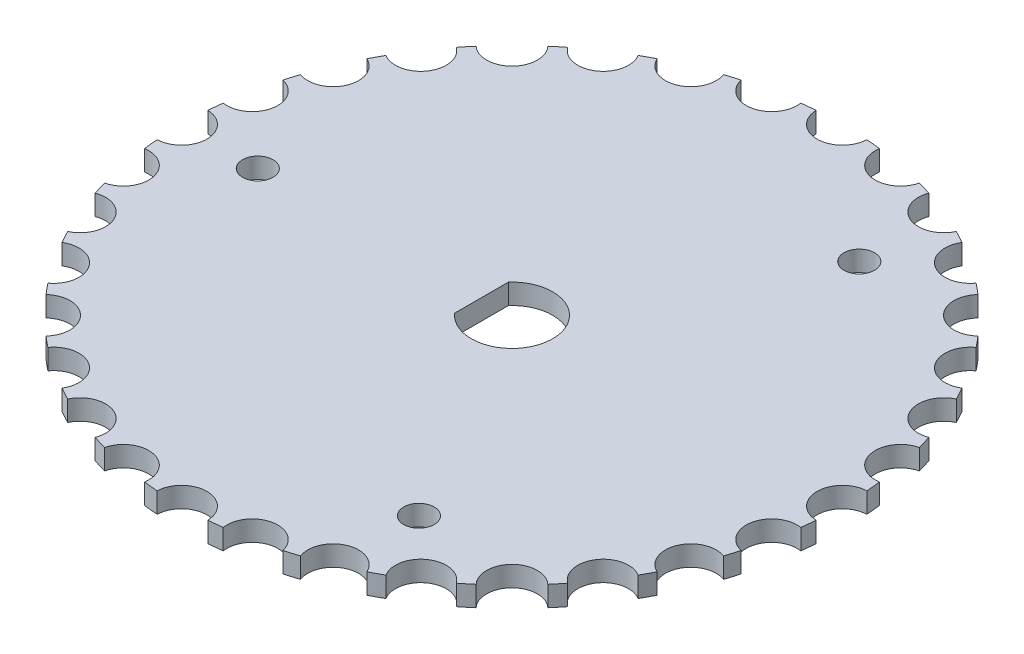
SolidWorks part; units mm, degrees
ref_plane "Front Plane" through (0, 0, 0) normal (0, 0, 1) x (1, 0, 0)
ref_plane "Top Plane" through (0, 0, 0) normal (0, 1, 0) x (1, 0, 0)
ref_plane "Right Plane" through (0, 0, 0) normal (1, 0, 0) x (0, 0, -1)
sketch "Sketch1" plane through (0, 0, 0) normal (0, 1, 0) x (1, 0, 0)
  circle A0 centre (0, 0) radius 32.5
  dimension "D1" = 65
extrude "Boss-Extrude1" add sketch "Sketch1" along normal blind 2
sketch "Sketch4" plane through (0, 2, 0) normal (0, 1, 0) x (1, 0, 0)
  line L0 (-3, -2.6458) -> (-3, 2.6458)
  arc A0 (-3, -2.6458) -> (-3, 2.6458) centre (0, 0) ccw
  dimension "D1" = 8
  dimension "D2" = 3
extrude "Cut-Extrude2" cut sketch "Sketch4" against normal through all
sketch "Sketch2" plane through (0, 2, 0) normal (0, 1, 0) x (1, 0, 0)
  circle A1 centre (-30.0261, -12.4372) radius 2.5
  circle A31 centre (-32.5, 0) radius 2.5
  circle A32 centre (0, 0) radius 32.5 construction
  circle A33 centre (-31.8755, 6.3404) radius 2.5
  circle A34 centre (-30.0261, 12.4372) radius 2.5
  circle A35 centre (-27.0228, 18.056) radius 2.5
  circle A36 centre (-22.981, 22.981) radius 2.5
  circle A37 centre (-18.056, 27.0228) radius 2.5
  circle A38 centre (-12.4372, 30.0261) radius 2.5
  circle A39 centre (-6.3404, 31.8755) radius 2.5
  circle A40 centre (0, 32.5) radius 2.5
  circle A41 centre (6.3404, 31.8755) radius 2.5
  circle A42 centre (12.4372, 30.0261) radius 2.5
  circle A43 centre (18.056, 27.0228) radius 2.5
  circle A44 centre (22.981, 22.981) radius 2.5
  circle A45 centre (27.0228, 18.056) radius 2.5
  circle A46 centre (30.0261, 12.4372) radius 2.5
  circle A47 centre (31.8755, 6.3404) radius 2.5
  circle A48 centre (32.5, 0) radius 2.5
  circle A49 centre (31.8755, -6.3404) radius 2.5
  circle A50 centre (30.0261, -12.4372) radius 2.5
  circle A51 centre (27.0228, -18.056) radius 2.5
  circle A52 centre (22.981, -22.981) radius 2.5
  circle A53 centre (18.056, -27.0228) radius 2.5
  circle A54 centre (12.4372, -30.0261) radius 2.5
  circle A55 centre (6.3404, -31.8755) radius 2.5
  circle A56 centre (0, -32.5) radius 2.5
  circle A57 centre (-6.3404, -31.8755) radius 2.5
  circle A58 centre (-12.4372, -30.0261) radius 2.5
  circle A59 centre (-18.056, -27.0228) radius 2.5
  circle A60 centre (-22.981, -22.981) radius 2.5
  circle A61 centre (-27.0228, -18.056) radius 2.5
  circle A62 centre (-31.8755, -6.3404) radius 2.5
  dimension "D1" = 5
  dimension "D2" = 32
extrude "Cut-Extrude1" cut sketch "Sketch2" against normal through all
sketch "Sketch5" plane through (0, 2, 0) normal (0, 1, 0) x (1, 0, 0)
  circle A0 centre (0, 0) radius 25 construction
  circle A1 centre (-25, 0) radius 1.5
  circle A2 centre (12.5, 21.6506) radius 1.5
  circle A3 centre (12.5, -21.6506) radius 1.5
  dimension "D1" = 50
  dimension "D2" = 3
extrude "Cut-Extrude3" cut sketch "Sketch5" against normal blind 10
